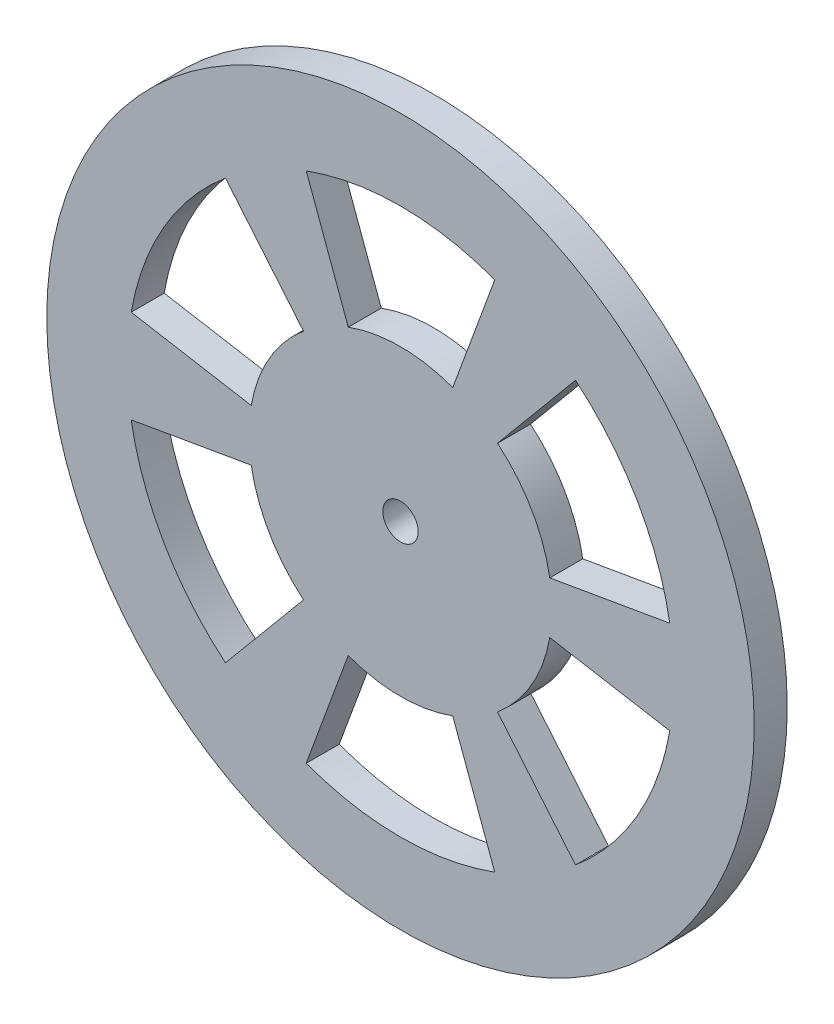
SolidWorks part; units mm, degrees
ref_plane "Front Plane" through (0, 0, 0) normal (0, 0, 1) x (1, 0, 0)
ref_plane "Top Plane" through (0, 0, 0) normal (0, 1, 0) x (1, 0, 0)
ref_plane "Right Plane" through (0, 0, 0) normal (1, 0, 0) x (0, 0, -1)
sketch "Model" plane through (0, 0, 0) normal (0, 0, 1) x (1, 0, 0)
  line L0 (160.1843, 5.5949) -> (170.362, 3.8318)
  line L1 (160.1834, -2.312) -> (170.3614, -0.5513)
  line L2 (168.1769, -16.161) -> (174.7926, -8.2284)
  line L3 (175.024, -20.1153) -> (178.5883, -10.4205)
  line L4 (191.0144, -20.1172) -> (187.4524, -10.4215)
  line L5 (197.8624, -16.1645) -> (191.2486, -8.2304)
  line L6 (205.8593, -2.3174) -> (195.6816, -0.5543)
  line L7 (205.8602, 5.5895) -> (195.6821, 3.8288)
  line L8 (197.8667, 19.4385) -> (191.251, 11.5059)
  line L9 (191.0196, 23.3928) -> (187.4553, 13.698)
  line L10 (175.0292, 23.3947) -> (178.5911, 13.699)
  line L11 (168.1811, 19.442) -> (174.795, 11.5079)
  circle A96 centre (183.0218, 1.6387) radius 1.5
  circle A97 centre (183.0218, 1.6387) radius 30
  arc A98 (170.3614, -0.5513) -> (174.7926, -8.2284) centre (183.0218, 1.6387) ccw
  arc A99 (178.5883, -10.4205) -> (187.4524, -10.4215) centre (183.0218, 1.6387) ccw
  arc A100 (175.024, -20.1153) -> (191.0144, -20.1172) centre (183.0218, 1.6387) ccw
  arc A101 (160.1834, -2.312) -> (168.1769, -16.161) centre (183.0218, 1.6387) ccw
  arc A102 (168.1811, 19.442) -> (160.1843, 5.5949) centre (183.0218, 1.6387) ccw
  arc A103 (174.795, 11.5079) -> (170.362, 3.8318) centre (183.0218, 1.6387) ccw
  arc A104 (191.2486, -8.2304) -> (195.6816, -0.5543) centre (183.0218, 1.6387) ccw
  arc A105 (197.8624, -16.1645) -> (205.8593, -2.3174) centre (183.0218, 1.6387) ccw
  arc A106 (205.8602, 5.5895) -> (197.8667, 19.4385) centre (183.0218, 1.6387) ccw
  arc A107 (195.6821, 3.8288) -> (191.251, 11.5059) centre (183.0218, 1.6387) ccw
  arc A108 (191.0196, 23.3928) -> (175.0292, 23.3947) centre (183.0218, 1.6387) ccw
  arc A109 (187.4553, 13.698) -> (178.5911, 13.699) centre (183.0218, 1.6387) ccw
extrude "Boss-Extrude1" add sketch "Model" along normal blind 2.8
